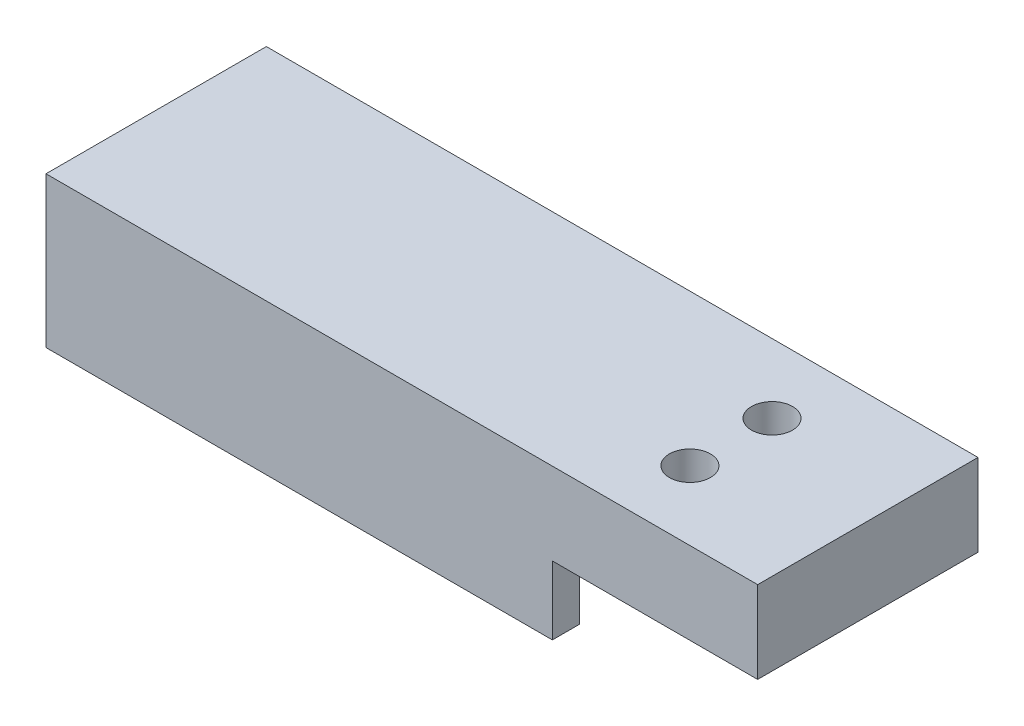
SolidWorks part; units mm, degrees
ref_plane "Front Plane" through (0, 0, 0) normal (0, 0, 1) x (1, 0, 0)
ref_plane "Top Plane" through (0, 0, 0) normal (0, 1, 0) x (1, 0, 0)
ref_plane "Right Plane" through (0, 0, 0) normal (1, 0, 0) x (0, 0, -1)
sketch "Sketch2" plane through (0, 0, 0) normal (0, 1, 0) x (1, 0, 0)
  line L0 (-27, 8.05) -> (25, 8.05)
  line L6 (-27, -8.05) -> (25, -8.05)
  line L7 (-21.55, 6.05) -> (25, 6.05)
  line L9 (-21.55, -6.05) -> (25, -6.05)
  line L11 (-25, 6.05) -> (25, -6.05) construction
  line L12 (-25, -6.05) -> (25, 6.05) construction
  line L13 (-27, 8.05) -> (-27, -8.05)
  line L14 (-25, 2.6) -> (-21.55, 6.05)
  line L15 (-25, -2.6) -> (-21.55, -6.05)
  line L16 (-25, 2.6) -> (-25, -2.6)
  line L17 (-25, 6.05) -> (-25, -6.05) construction
  line L18 (-25, 6.05) -> (25, 6.05) construction
  line L19 (-25, -6.05) -> (25, -6.05) construction
  line L20 (-27, 0) -> (-25, 0) construction
  line L21 (25, 6.05) -> (25, 8.05)
  line L22 (27, 8.05) -> (27, -8.05) construction
  line L23 (25, 6.05) -> (25, -6.05) construction
  line L24 (25, -6.05) -> (25, -8.05)
  line L25 (-27, -8.05) -> (27, -8.05) construction
  line L26 (-27, 8.05) -> (27, 8.05) construction
  point P0 (0, 0)
  point P5 (0, 0)
  dimension "D1" = 12.1
  dimension "D2" = 50
  dimension "D4" = 2
  dimension "D5" = 5.2
  dimension "D6" = 135
  dimension "D7" = 135
  dimension "D3" = 2
extrude "Boss-Extrude1" add sketch "Sketch2" along normal blind 5
sketch "Sketch3" plane through (0, 5, 0) normal (0, 1, 0) x (1, 0, 0)
  line L0 (25, 6.05) -> (25, -6.05)
  line L10 (-25, -2.6) -> (-25, 2.6)
  line L11 (-25, 2.6) -> (-21.55, 6.05)
  line L12 (-21.55, 6.05) -> (25, 6.05)
  line L13 (25, 6.05) -> (25, 8.05)
  line L14 (25, 8.05) -> (-27, 8.05)
  line L15 (-27, 8.05) -> (-27, -8.05)
  line L16 (-27, -8.05) -> (25, -8.05)
  line L17 (25, -8.05) -> (25, -6.05)
  line L18 (25, -6.05) -> (-21.55, -6.05)
  line L19 (-21.55, -6.05) -> (-25, -2.6)
  line L23 (25, 6.05) -> (25, 8.05)
  line L24 (25, 8.05) -> (-27, 8.05)
  line L25 (-27, 8.05) -> (-27, -8.05)
  line L26 (-27, -8.05) -> (25, -8.05)
  line L27 (25, -8.05) -> (25, -6.05)
  dimension "D1" = 0
extrude "Boss-Extrude2" add sketch "Sketch3" along normal blind 6
sketch "Sketch4" plane through (0, 5, 0) normal (0, -1, 0) x (1, 0, 0)
  line L0 (-25, 0) -> (15, 0) construction
  line L1 (-25, 2.6) -> (-25, -2.6) construction
  line L2 (15, 3) -> (15, -3) construction
  circle A0 centre (15, 3) radius 1.5
  circle A1 centre (15, -3) radius 1.5
  dimension "D2" = 3
  dimension "D3" = 3
  dimension "D1" = 6
  dimension "D4" = 40
extrude "Cut-Extrude1" cut sketch "Sketch4" against normal through all
sketch "Sketch5" plane through (0, 0, 6.05) normal (0, 0, -1) x (-1, 0, 0)
  line L0 (-25, 0) -> (21.55, 0) construction
  line L1 (-25, 5) -> (-10, 5)
  line L2 (-25, 5) -> (-25, 0)
  line L3 (-25, 0) -> (-10, 0)
  line L4 (-10, 5) -> (-10, 0)
  line L6 (25, 5) -> (25, 0) construction
  dimension "D1" = 35
extrude "Cut-Extrude2" cut sketch "Sketch5" against normal through all both and the other way through all
sketch "Sketch6" plane through (0, 11, 0) normal (0, 1, 0) x (1, 0, 0)
  circle A0 centre (15, 3) radius 2.5
  circle A1 centre (15, 3) radius 1.5 construction
  circle A2 centre (15, 3) radius 1.5
  circle A3 centre (15, -3) radius 1.5 construction
  circle A4 centre (15, -3) radius 1.5
  circle A5 centre (15, -3) radius 2.5
  dimension "D1" = 5
  dimension "D2" = 5
